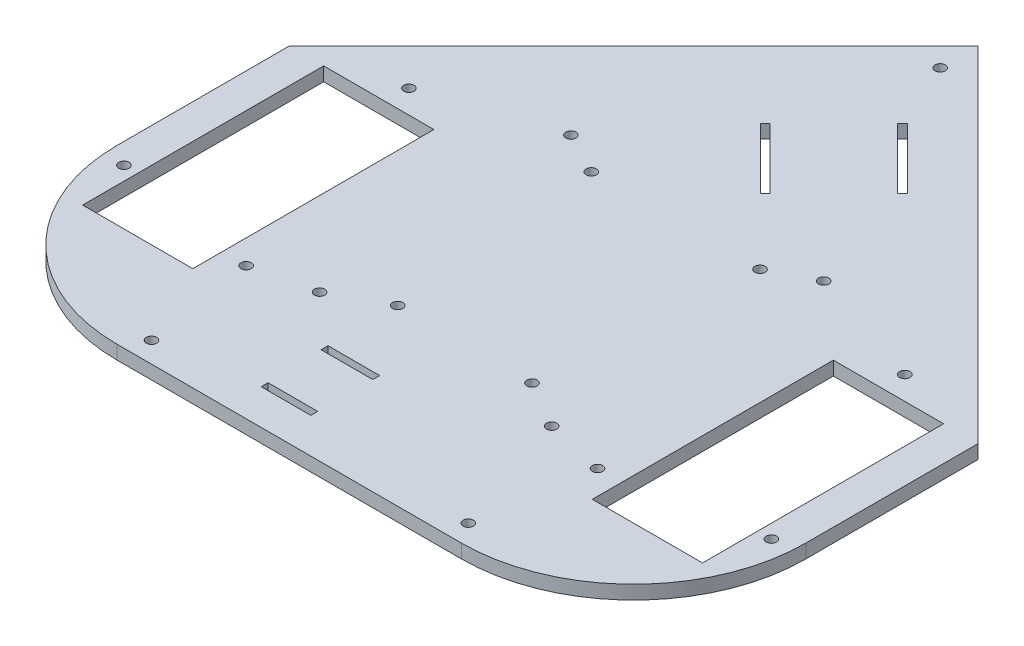
SolidWorks part; units mm, degrees
material "multiplex"
ref_plane "Front Plane" through (0, 0, 0) normal (0, 0, 1) x (1, 0, 0)
ref_plane "Top Plane" through (0, 0, 0) normal (0, 1, 0) x (1, 0, 0)
ref_plane "Right Plane" through (0, 0, 0) normal (1, 0, 0) x (0, 0, -1)
sketch "basis_grondplaat_schets" plane through (0, 0, 0) normal (0, 1, 0) x (1, 0, 0)
  line L0 (-100, 50) -> (100, 50) construction
  line L1 (-50, -50) -> (50, -50)
  line L2 (-100, 0) -> (-100, 50)
  line L4 (100, 0) -> (100, 50)
  line L5 (-100, -50) -> (100, 50) construction
  line L6 (-100, 50) -> (100, -50) construction
  line L7 (0, 50) -> (0, 150) construction
  line L8 (-100, 50) -> (0, 150)
  line L9 (0, 150) -> (100, 50)
  arc A0 (50, -50) -> (100, 0) centre (50, 0) ccw
  arc A1 (-50, -50) -> (-100, 0) centre (-50, 0) cw
  point P0 (0, 0)
  dimension "D3" = 50
  dimension "D1" = 200
  dimension "D2" = 100
  dimension "D4" = 100
extrude "basis_grondplaat" add sketch "basis_grondplaat_schets" along normal blind 4
sketch "wielgaten_schets" plane through (0, 4, 0) normal (0, 1, 0) x (1, 0, 0)
  line L0 (-100, 0) -> (100, 0) construction
  line L5 (0, 0) -> (0, 150) construction
  line L6 (-100, 50) -> (100, 50) construction
  line L10 (-90, 50) -> (-90, -20) construction
  line L11 (-100, 50) -> (-100, 0) construction
  line L15 (-90, 50) -> (-90, -20)
  line L17 (-58, 50) -> (-90, 50)
  line L24 (-58, 50) -> (-58, -20)
  line L30 (-90, -20) -> (-58, -20)
  dimension "D1" = 10
  dimension "D3" = 70
  dimension "D6" = 32
extrude "wielgaten" cut sketch "wielgaten_schets" against normal blind 10
sketch "boorgat1_schets" plane through (0, 0, 0) normal (0, -1, 0) x (1, 0, 0)
  circle A0 centre (-46, 44) radius 1.5
  dimension "D1" = 3
extrude "boorgat1" cut sketch "boorgat1_schets" against normal through all
mirror "Mirror1" about plane through (0, 0, 0) normal (1, 0, 0) of "wielgaten"
sketch "Sketch1" plane through (0, 0, 0) normal (0, -1, 0) x (-1, 0, 0)
  line L0 (10.7519, 100.3781) -> (-6.9258, 82.7005)
  line L1 (10.7519, 100.3781) -> (12.1661, 98.9639)
  line L2 (-6.9258, 82.7005) -> (-5.5116, 81.2862)
  line L3 (12.1661, 98.9639) -> (-5.5116, 81.2862)
  line L4 (17.823, 107.4492) -> (-12.4059, 77.2204) construction
  line L5 (16.4087, 108.8634) -> (0.711, 124.5612) construction
  line L8 (-25.452, 101.2266) -> (-7.7743, 118.9043)
  line L9 (-25.452, 101.2266) -> (-26.8662, 102.6409)
  line L10 (-7.7743, 118.9043) -> (-9.1885, 120.3185)
  line L11 (-26.8662, 102.6409) -> (-9.1885, 120.3185)
  line L12 (-0.7032, 125.9754) -> (-30.9321, 95.7466) construction
  line L13 (4, -21.75) -> (19, -21.75)
  line L14 (4, -21.75) -> (4, -19.75)
  line L15 (19, -21.75) -> (19, -19.75)
  line L16 (4, -19.75) -> (19, -19.75)
  line L17 (-8, -21.75) -> (29, -21.75) construction
  line L18 (4, -37.75) -> (18.4, -37.75)
  line L19 (4, -37.75) -> (4, -39.75)
  line L20 (18.4, -37.75) -> (18.4, -39.75)
  line L21 (4, -39.75) -> (18.4, -39.75)
  line L22 (29, -37.75) -> (-8, -37.75) construction
  line L23 (29, -21.75) -> (29, -37.75) construction
  circle A0 centre (-46, -44) radius 1.5
  circle A1 centre (-94, -4) radius 1.5
  circle A2 centre (94, -4) radius 1.5
  circle A3 centre (0, 139) radius 1.5
  circle A8 centre (24.5, 62.2) radius 1.5
  circle A9 centre (-24.5, 62.2) radius 1.5
  circle A10 centre (-20, 0.5) radius 1.5
  circle A11 centre (19, 0.5) radius 1.5
  dimension "D1" = 3
  dimension "D2" = 3
  dimension "D3" = 3
  dimension "D4" = 3
  dimension "D5" = 2
  dimension "D6" = 25
  dimension "D7" = 10
  dimension "D8" = 2
  dimension "D13" = 3
  dimension "D14" = 3
  dimension "D15" = 3
  dimension "D16" = 3
  dimension "D9" = 2
  dimension "D10" = 2
  dimension "D11" = 10
  dimension "D12" = 15
extrude "Cut-Extrude1" cut sketch "Sketch1" against normal blind 10
sketch "Sketch2" plane through (0, 0, 0) normal (0, -1, 0) x (-1, 0, 0)
  circle A0 centre (51, -11.5) radius 1.5
  circle A1 centre (33.7, -7.5) radius 1.5
  circle A2 centre (-33.7, -7.5) radius 1.5
  circle A3 centre (-51, -11.5) radius 1.5
  circle A4 centre (36.7, 68.5) radius 1.5
  circle A5 centre (-36.7, 68.5) radius 1.5
  circle A6 centre (-72, 56.75) radius 1.5
  circle A7 centre (72, 56.75) radius 1.5
  dimension "D1" = 3
  dimension "D2" = 3
  dimension "D3" = 3
  dimension "D4" = 3
  dimension "D5" = 3
  dimension "D6" = 3
  dimension "D7" = 3
  dimension "D8" = 3
extrude "Cut-Extrude2" cut sketch "Sketch2" against normal blind 10
